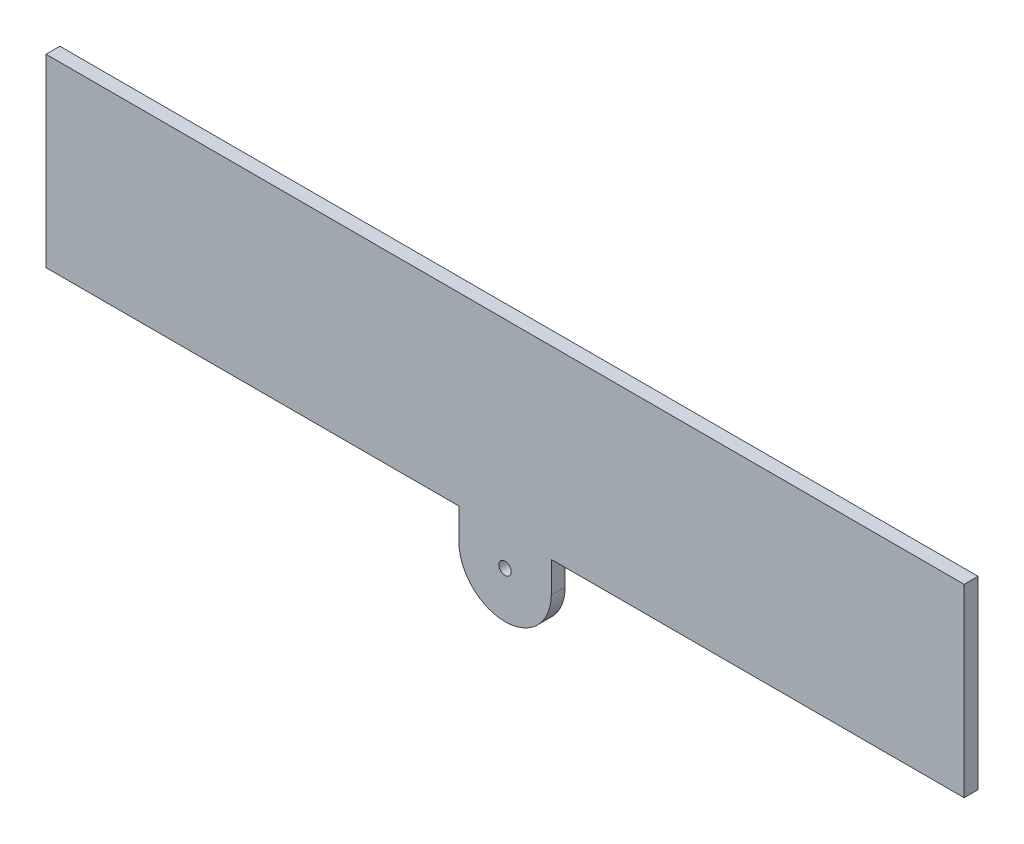
SolidWorks part; units mm, degrees
ref_plane "Front Plane" through (0, 0, 0) normal (0, 0, 1) x (1, 0, 0)
ref_plane "Top Plane" through (0, 0, 0) normal (0, 1, 0) x (1, 0, 0)
ref_plane "Right Plane" through (0, 0, 0) normal (1, 0, 0) x (0, 0, -1)
sketch "Sketch1" plane through (0, 0, 0) normal (0, 0, 1) x (1, 0, 0)
  line L1 (-37.846, 7.62) -> (37.846, 7.62)
  line L2 (-37.846, 7.62) -> (-37.846, -7.62)
  line L3 (-37.846, -7.62) -> (37.846, -7.62)
  line L4 (37.846, 7.62) -> (37.846, -7.62)
  line L5 (-37.846, 7.62) -> (37.846, -7.62) construction
  line L6 (-37.846, -7.62) -> (37.846, 7.62) construction
  point P0 (0, 0)
  dimension "D1" = 15.24
  dimension "D2" = 75.692
extrude "Boss-Extrude1" add sketch "Sketch1" along normal blind 1.143
sketch "Sketch2" plane through (0, 0, 1.143) normal (0, 0, 1) x (1, 0, 0)
  line L0 (-3.81, -7.62) -> (3.81, -7.62)
  line L1 (-3.81, -7.62) -> (-3.81, -10.16)
  line L2 (3.81, -7.62) -> (3.81, -10.16)
  line L4 (-37.846, -7.62) -> (37.846, -7.62) construction
  arc A0 (-3.81, -10.16) -> (3.81, -10.16) centre (0, -10.16) ccw
  circle A1 centre (0, -10.16) radius 0.508
  point P7 (3.81, -10.5689)
  dimension "D1" = 1.016
  dimension "D2" = 7.62
  dimension "D3" = 2.54
extrude "Boss-Extrude2" add sketch "Sketch2" against normal up to surface (1.143 mm away) up to face at (0, 0, 0)
